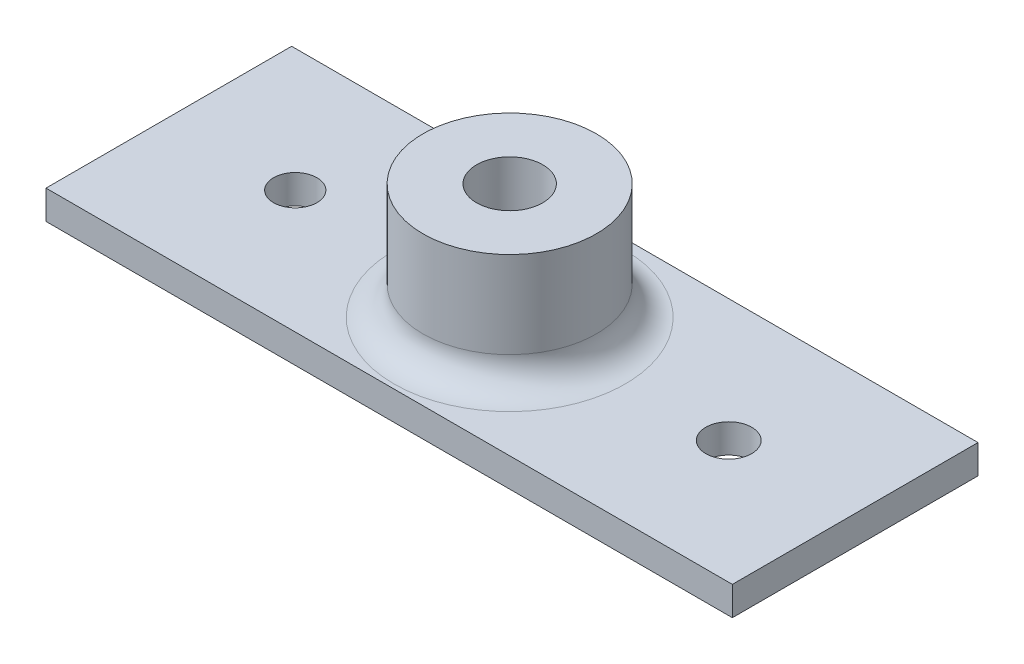
SolidWorks part; units mm, degrees
ref_plane "Front Plane" through (0, 0, 0) normal (0, 0, 1) x (1, 0, 0)
ref_plane "Top Plane" through (0, 0, 0) normal (0, 1, 0) x (1, 0, 0)
ref_plane "Right Plane" through (0, 0, 0) normal (1, 0, 0) x (0, 0, -1)
sketch "Sketch1" plane through (0, 0, 0) normal (0, 1, 0) x (1, 0, 0)
  line L1 (-36.5281, 15.1352) -> (10.9719, 15.1352)
  line L2 (-36.5281, 15.1352) -> (-36.5281, -1.8648)
  line L3 (-36.5281, -1.8648) -> (10.9719, -1.8648)
  line L4 (10.9719, 15.1352) -> (10.9719, -1.8648)
  line L5 (-36.5281, 15.1352) -> (10.9719, -1.8648) construction
  line L6 (-36.5281, -1.8648) -> (10.9719, 15.1352) construction
  point P0 (-12.7781, 6.6352)
  dimension "D1" = 17
  dimension "D2" = 47.5
extrude "Boss-Extrude1" add sketch "Sketch1" along normal blind 2
sketch "Sketch2" plane through (0, 2, 0) normal (0, 1, 0) x (1, 0, 0)
  line L0 (-36.5281, -1.8648) -> (10.9719, -1.8648) construction
  circle A0 centre (-12.7781, 6.6352) radius 6
  circle A1 centre (-12.7781, 6.6352) radius 2.4872
  circle A2 centre (2.2219, 6.6352) radius 1.5863
  circle A3 centre (-27.7781, 6.6352) radius 1.5
  dimension "D1" = 12
  dimension "D3" = 3
  dimension "D2" = 8.5
  dimension "D4" = 15
  dimension "D5" = 15
extrude "Cut-Extrude2" cut sketch "Sketch2" against normal blind 2 contours A3 | A1 | A2
sketch "Sketch5" plane through (0, 2, 0) normal (0, 1, 0) x (1, 0, 0)
  circle A0 centre (-12.7416, 6.4381) radius 2.2868
  circle A1 centre (-12.7416, 6.4381) radius 6
  dimension "D1" = 12
extrude "Boss-Extrude3" add sketch "Sketch5" along normal blind 8
fillet "Fillet1" radius 2 1 edges at (-12.7416, 2, -0.4381)
